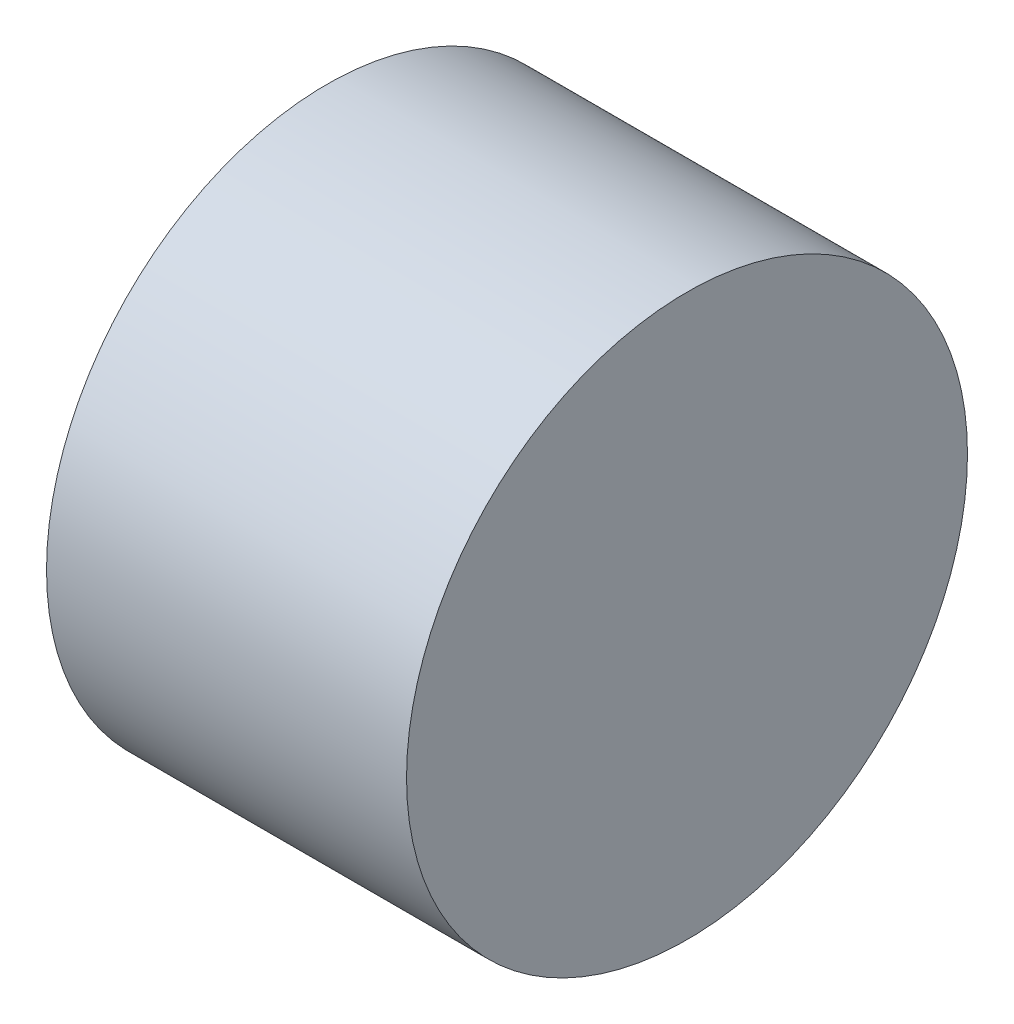
SolidWorks part; units mm, degrees
ref_plane "前视基准面" through (0, 0, 0) normal (0, 0, 1) x (1, 0, 0)
ref_plane "上视基准面" through (0, 0, 0) normal (0, 1, 0) x (1, 0, 0)
ref_plane "右视基准面" through (0, 0, 0) normal (1, 0, 0) x (0, 0, -1)
sketch "草图5" plane through (0, 0, 0) normal (1, 0, 0) x (0, 0, -1)
  circle A0 centre (0, 0) radius 16.75
  dimension "D1" = 33.5
extrude "凸台-拉伸4" add sketch "草图5" along normal blind 21.5
